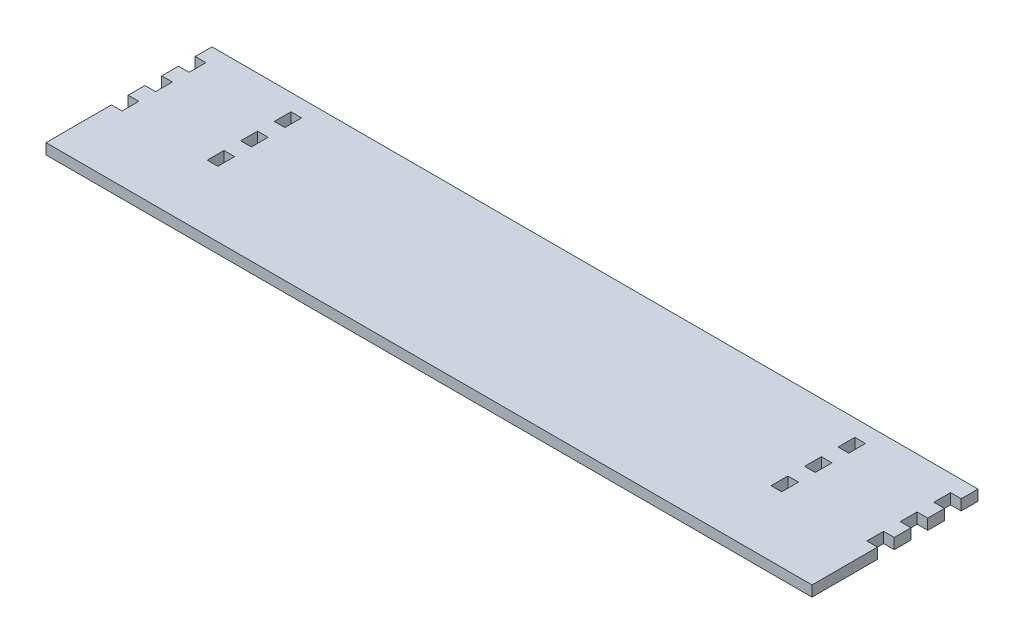
SolidWorks part; units mm, degrees
ref_plane "Front Plane" through (0, 0, 0) normal (0, 0, 1) x (1, 0, 0)
ref_plane "Top Plane" through (0, 0, 0) normal (0, 1, 0) x (1, 0, 0)
ref_plane "Right Plane" through (0, 0, 0) normal (1, 0, 0) x (0, 0, -1)
sketch "Sketch1" plane through (0, 0, 0) normal (0, 1, 0) x (1, 0, 0)
  line L0 (-228.6, -5) -> (-225.425, -5)
  line L1 (-19.177, 0) -> (-225.425, 0)
  line L2 (-196.85, -5) -> (-196.85, 0) construction
  line L3 (-19.177, -49.53) -> (-225.425, -49.53)
  line L4 (-228.6, -30) -> (-228.6, -49.53)
  line L5 (-3.175, -25) -> (-3.175, -30)
  line L6 (-228.6, -5) -> (-228.6, 0)
  line L7 (-228.6, 0) -> (-225.425, 0)
  line L8 (-228.6, -10) -> (-225.425, -10)
  line L9 (-3.175, -15) -> (-3.175, -20)
  line L10 (-3.175, -5) -> (-3.175, -10)
  line L11 (-225.425, -15) -> (-228.6, -15)
  line L12 (0, -20) -> (0, -25)
  line L13 (-228.6, -20) -> (-225.425, -20)
  line L14 (0, -10) -> (0, -15)
  line L15 (-225.425, -25) -> (-228.6, -25)
  line L16 (-228.6, -49.53) -> (-225.425, -49.53)
  line L17 (-228.6, -30) -> (-225.425, -30)
  line L18 (0, -30) -> (-3.175, -30)
  line L19 (-200.025, -5) -> (-196.85, -5)
  line L20 (0, -49.53) -> (-19.177, -49.53)
  line L21 (-122.301, 0) -> (-122.301, -49.53) construction
  line L22 (-19.177, 0) -> (0, 0)
  line L23 (0, 0) -> (0, -5) construction
  line L24 (-228.6, -10) -> (-228.6, -15)
  line L25 (-228.6, -20) -> (-228.6, -25)
  line L26 (-200.025, -5) -> (-200.025, -10)
  line L27 (-200.025, -10) -> (-196.85, -10)
  line L28 (0, -30) -> (-3.175, -30)
  line L29 (-3.175, -25) -> (0, -25)
  line L30 (-196.85, -5) -> (-196.85, -10)
  line L31 (0, -20) -> (-3.175, -20)
  line L32 (-200.025, -15) -> (-196.85, -15)
  line L33 (-3.175, -15) -> (0, -15)
  line L34 (-200.025, -15) -> (-200.025, -20)
  line L35 (-200.025, -20) -> (-196.85, -20)
  line L36 (0, -10) -> (-3.175, -10)
  line L37 (-196.85, -15) -> (-196.85, -20)
  line L38 (0, -5) -> (-3.175, -5)
  line L39 (-225.425, -5) -> (-225.425, -10)
  line L40 (-225.425, -15) -> (-225.425, -20)
  line L41 (-225.425, -25) -> (-225.425, -30)
  line L42 (-3.175, -25) -> (0, -25)
  line L43 (0, -20) -> (-3.175, -20)
  line L44 (-3.175, -15) -> (0, -15)
  line L45 (0, -10) -> (-3.175, -10)
  line L46 (0, 0) -> (-19.177, 0) construction
  line L47 (0, -5) -> (0, 0)
  line L48 (0, -30) -> (0, -49.53)
  line L49 (0, -5) -> (-3.175, -5)
  line L50 (-200.025, -25) -> (-196.85, -25)
  line L51 (-200.025, -25) -> (-200.025, -30)
  line L52 (-200.025, -30) -> (-196.85, -30)
  line L53 (-196.85, -25) -> (-196.85, -30)
  line L54 (-196.85, -10) -> (-196.85, -15) construction
  line L55 (-196.85, -20) -> (-196.85, -25) construction
  line L56 (-31.75, -20) -> (-31.75, -25) construction
  line L57 (-31.75, -10) -> (-31.75, -15) construction
  line L58 (-31.75, -5) -> (-31.75, 0) construction
  line L59 (-31.75, -25) -> (-31.75, -30)
  line L60 (-28.575, -30) -> (-31.75, -30)
  line L61 (-28.575, -25) -> (-28.575, -30)
  line L62 (-28.575, -25) -> (-31.75, -25)
  line L63 (-31.75, -15) -> (-31.75, -20)
  line L64 (-28.575, -20) -> (-31.75, -20)
  line L65 (-28.575, -15) -> (-28.575, -20)
  line L66 (-28.575, -15) -> (-31.75, -15)
  line L67 (-31.75, -5) -> (-31.75, -10)
  line L68 (-28.575, -10) -> (-31.75, -10)
  line L69 (-28.575, -5) -> (-28.575, -10)
  line L70 (-28.575, -5) -> (-31.75, -5)
  dimension "D1" = 5
  dimension "D2" = 228.6
  dimension "D3" = 3.175
  dimension "D4" = 5
  dimension "D5" = 49.53
  dimension "D6" = 5
  dimension "D7" = 5
  dimension "D8" = 3.175
  dimension "D9" = 25.4
  dimension "D10" = 25.4
  dimension "D11" = 3.175
extrude "Boss-Extrude1" add sketch "Sketch1" along normal blind 3.175 contours L48 L18 L5 L29 L12 L31 L9 L33 L14 L36 L10 L38 L47 L46 L1 L7 L6 L0 L39 L8 L24 L11 L40 L13 L25 L15 L41 L17 L4 L16 L3 L20
